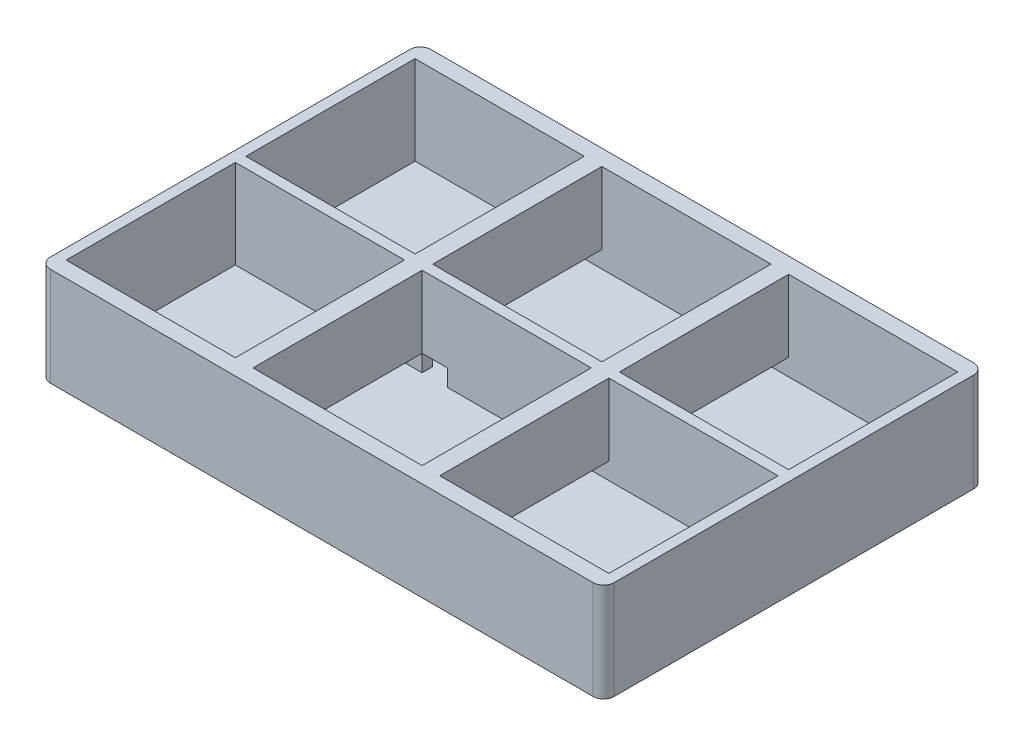
SolidWorks part; units mm, degrees
ref_plane "Front Plane" through (0, 0, 0) normal (0, 0, 1) x (1, 0, 0)
ref_plane "Top Plane" through (0, 0, 0) normal (0, 1, 0) x (1, 0, 0)
ref_plane "Right Plane" through (0, 0, 0) normal (1, 0, 0) x (0, 0, -1)
sketch "Sketch1" plane through (0, 0, 0) normal (0, 1, 0) x (1, 0, 0)
  line L1 (200, 135) -> (-200, 135)
  line L2 (200, 135) -> (200, -135)
  line L3 (200, -135) -> (-200, -135)
  line L4 (-200, 135) -> (-200, -135)
  line L5 (200, 135) -> (-200, -135) construction
  line L6 (200, -135) -> (-200, 135) construction
  point P0 (0, 0)
  dimension "D1" = 400
  dimension "D2" = 270
extrude "Boss-Extrude1" add sketch "Sketch1" along normal blind 70
fillet "Fillet1" radius 7.5 4 edges at (200, 35, -135) (200, 35, 135) (-200, 35, -135) (-200, 35, 135)
sketch "Sketch2" plane through (0, 70, 0) normal (0, 1, 0) x (1, 0, 0)
  line L0 (-192.5, 135) -> (-192.5, -135) construction
  line L1 (200, -127.5) -> (-200, -127.5) construction
  line L2 (192.5, 135) -> (192.5, -135) construction
  line L3 (200, 127.5) -> (-200, 127.5) construction
  line L4 (-200, 0) -> (200, 0) construction
  line L5 (192.5, 135) -> (-192.5, 135) construction
  line L6 (0, 135) -> (0, -135) construction
  line L7 (-192.5, -135) -> (192.5, -135) construction
  line L8 (-200, 127.5) -> (-200, -127.5) construction
  line L9 (200, -127.5) -> (200, 127.5) construction
  arc A0 (-200, -127.5) -> (-192.5, -135) centre (-192.5, -127.5) ccw construction
  arc A1 (200, 127.5) -> (192.5, 135) centre (192.5, 127.5) ccw construction
sketch "Sketch3" plane through (0, 70, 0) normal (0, 1, 0) x (1, 0, 0)
  line L0 (0, 0) -> (0, 127.4989) construction
  line L1 (-200, 0) -> (200, 0) construction
  line L2 (60, 123.7495) -> (-60, 123.7495)
  line L3 (60, 123.7495) -> (60, 3.7495)
  line L4 (60, 3.7495) -> (-60, 3.7495)
  line L6 (60, 123.7495) -> (-60, 3.7495) construction
  line L7 (60, 3.7495) -> (-60, 123.7495) construction
  line L14 (-60, 123.7495) -> (-60, 3.7495)
  line L15 (-72.5, 123.7495) -> (-192.5, 123.7495)
  line L16 (-72.5, 123.7495) -> (-72.5, 3.7495)
  line L17 (-72.5, 3.7495) -> (-192.5, 3.7495)
  line L18 (-192.5, 123.7495) -> (-192.5, 3.7495)
  line L19 (192.5, 123.7495) -> (72.5, 123.7495)
  line L20 (192.5, 123.7495) -> (192.5, 3.7495)
  line L21 (192.5, 3.7495) -> (72.5, 3.7495)
  line L22 (72.5, 123.7495) -> (72.5, 3.7495)
  line L23 (192.5, -3.7495) -> (72.5, -3.7495)
  line L24 (192.5, -123.7495) -> (192.5, -3.7495)
  line L25 (192.5, -123.7495) -> (72.5, -123.7495)
  line L26 (72.5, -123.7495) -> (72.5, -3.7495)
  line L27 (60, -3.7495) -> (-60, -3.7495)
  line L28 (60, -123.7495) -> (60, -3.7495)
  line L29 (60, -123.7495) -> (-60, -123.7495)
  line L30 (-60, -123.7495) -> (-60, -3.7495)
  line L31 (-192.5, -123.7495) -> (-192.5, -3.7495)
  line L32 (-72.5, -123.7495) -> (-192.5, -123.7495)
  line L33 (-72.5, -123.7495) -> (-72.5, -3.7495)
  line L34 (-72.5, -3.7495) -> (-192.5, -3.7495)
  point P3 (0, 63.7495)
  dimension "D2" = 120
  dimension "D3" = 120
extrude "Cut-Extrude1" cut sketch "Sketch3" against normal blind 63
sketch "Sketch5" plane through (-72.5, 0, 0) normal (-1, 0, 0) x (0, 0, 1)
  line L0 (-123.7495, 7) -> (-123.7495, 70) construction
  line L1 (-123.7495, 7) -> (-3.7495, 7)
  line L2 (-123.7495, 7) -> (-123.7495, 19)
  line L3 (-123.7495, 19) -> (-3.7495, 19)
  line L4 (-3.7495, 7) -> (-3.7495, 19)
  line L5 (-3.7495, 7) -> (-123.7495, 7) construction
  line L6 (-3.7495, 7) -> (-3.7495, 70) construction
  dimension "D1" = 12
extrude "Cut-Extrude2" cut sketch "Sketch5" against normal blind 153
sketch "Sketch6" plane through (-72.5, 0, 0) normal (-1, 0, 0) x (0, 0, 1)
  line L0 (123.7495, 7) -> (123.7495, 70) construction
  line L1 (3.7495, 7) -> (123.7495, 7)
  line L2 (3.7495, 7) -> (3.7495, 19)
  line L3 (3.7495, 19) -> (123.7495, 19)
  line L4 (123.7495, 7) -> (123.7495, 19)
  dimension "D1" = 12
extrude "Cut-Extrude3" cut sketch "Sketch6" against normal blind 153
sketch "Sketch7" plane through (0, 0, 3.7495) normal (0, 0, 1) x (1, 0, 0)
  line L0 (192.5, 7) -> (-192.5, 7) construction
  line L1 (-60, 19) -> (-42, 19)
  line L2 (-60, 19) -> (-60, 7)
  line L3 (-60, 7) -> (-42, 7)
  line L4 (-42, 19) -> (-42, 7)
  line L6 (60, 19) -> (42, 19)
  line L7 (60, 19) -> (60, 7)
  line L8 (60, 7) -> (42, 7)
  line L9 (42, 19) -> (42, 7)
  dimension "D1" = 18
  dimension "D2" = 18
extrude "Cut-Extrude4" cut sketch "Sketch7" against normal up to next
